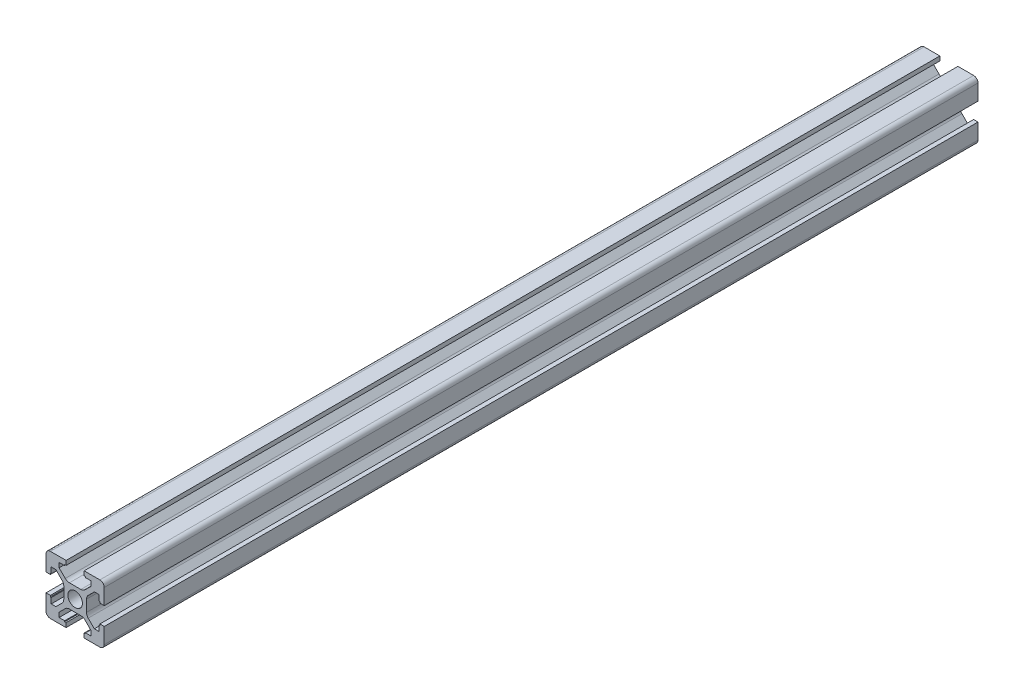
SolidWorks part; units mm, degrees
material "6063-T5"
ref_plane "Front Plane" through (0, 0, 0) normal (0, 0, 1) x (1, 0, 0)
ref_plane "Top Plane" through (0, 0, 0) normal (0, 1, 0) x (1, 0, 0)
ref_plane "Right Plane" through (0, 0, 0) normal (1, 0, 0) x (0, 0, -1)
sketch "Sketch1" plane through (0, 0, 0) normal (0, 0, 1) x (1, 0, 0)
  line L0 (0, 0) -> (0, 15) construction
  line L1 (-10, 10) -> (0, 10) construction
  line L2 (-10, 10) -> (-10, 0) construction
  line L3 (1.9716, 3.9) -> (-1.9716, 3.9)
  line L4 (-3.3858, 4.4858) -> (-5.5, 6.6)
  line L5 (0, 0) -> (-15, 0) construction
  line L6 (-5.5, 6.6) -> (-5.5, 8.2)
  line L7 (-5.5, 8.2) -> (-3.6, 8.2)
  line L8 (-3.6, 8.2) -> (-3.6, 8.5)
  line L9 (-3.6, 8.5) -> (-3.1, 8.5)
  line L10 (-3.1, 8.5) -> (-3.1, 10)
  line L11 (-3.1, 10) -> (-8.5, 10)
  line L12 (-10, 8.5) -> (-10, 3.1)
  line L13 (-10, 3.1) -> (-8.5, 3.1)
  line L14 (-8.5, 3.1) -> (-8.5, 3.6)
  line L15 (-8.5, 3.6) -> (-8.2, 3.6)
  line L16 (-8.2, 3.6) -> (-8.2, 5.5)
  line L17 (-8.2, 5.5) -> (-6.6, 5.5)
  line L18 (-6.6, 5.5) -> (-4.4858, 3.3858)
  line L19 (-3.9, 1.9716) -> (-3.9, -1.9716)
  line L20 (3.9, 1.9716) -> (3.9, -1.9716)
  line L21 (6.6, 5.5) -> (4.4858, 3.3858)
  line L22 (8.2, 5.5) -> (6.6, 5.5)
  line L23 (8.2, 3.6) -> (8.2, 5.5)
  line L24 (8.5, 3.6) -> (8.2, 3.6)
  line L25 (8.5, 3.1) -> (8.5, 3.6)
  line L26 (10, 3.1) -> (8.5, 3.1)
  line L27 (10, 8.5) -> (10, 3.1)
  line L28 (3.1, 10) -> (8.5, 10)
  line L29 (3.1, 8.5) -> (3.1, 10)
  line L30 (3.6, 8.5) -> (3.1, 8.5)
  line L31 (3.6, 8.2) -> (3.6, 8.5)
  line L32 (5.5, 8.2) -> (3.6, 8.2)
  line L33 (5.5, 6.6) -> (5.5, 8.2)
  line L34 (3.3858, 4.4858) -> (5.5, 6.6)
  line L35 (6.6, -5.5) -> (4.4858, -3.3858)
  line L36 (8.2, -5.5) -> (6.6, -5.5)
  line L37 (8.2, -3.6) -> (8.2, -5.5)
  line L38 (8.5, -3.6) -> (8.2, -3.6)
  line L39 (8.5, -3.1) -> (8.5, -3.6)
  line L40 (10, -3.1) -> (8.5, -3.1)
  line L41 (10, -8.5) -> (10, -3.1)
  line L42 (3.1, -10) -> (8.5, -10)
  line L43 (3.1, -8.5) -> (3.1, -10)
  line L44 (3.6, -8.5) -> (3.1, -8.5)
  line L45 (3.6, -8.2) -> (3.6, -8.5)
  line L46 (5.5, -8.2) -> (3.6, -8.2)
  line L47 (5.5, -6.6) -> (5.5, -8.2)
  line L48 (3.3858, -4.4858) -> (5.5, -6.6)
  line L49 (1.9716, -3.9) -> (-1.9716, -3.9)
  line L50 (-3.3858, -4.4858) -> (-5.5, -6.6)
  line L51 (-5.5, -6.6) -> (-5.5, -8.2)
  line L52 (-5.5, -8.2) -> (-3.6, -8.2)
  line L53 (-3.6, -8.2) -> (-3.6, -8.5)
  line L54 (-3.6, -8.5) -> (-3.1, -8.5)
  line L55 (-3.1, -8.5) -> (-3.1, -10)
  line L56 (-3.1, -10) -> (-8.5, -10)
  line L57 (-10, -8.5) -> (-10, -3.1)
  line L58 (-10, -3.1) -> (-8.5, -3.1)
  line L59 (-8.5, -3.1) -> (-8.5, -3.6)
  line L60 (-8.5, -3.6) -> (-8.2, -3.6)
  line L61 (-8.2, -3.6) -> (-8.2, -5.5)
  line L62 (-8.2, -5.5) -> (-6.6, -5.5)
  line L63 (-6.6, -5.5) -> (-4.4858, -3.3858)
  circle A0 centre (0, 0) radius 2.5
  arc A1 (-10, -8.5) -> (-8.5, -10) centre (-8.5, -8.5) ccw
  arc A2 (8.5, -10) -> (10, -8.5) centre (8.5, -8.5) ccw
  arc A3 (10, 8.5) -> (8.5, 10) centre (8.5, 8.5) ccw
  arc A4 (-8.5, 10) -> (-10, 8.5) centre (-8.5, 8.5) ccw
  arc A5 (-3.3858, -4.4858) -> (-1.9716, -3.9) centre (-1.9716, -5.9) cw
  arc A6 (1.9716, -3.9) -> (3.3858, -4.4858) centre (1.9716, -5.9) cw
  arc A7 (4.4858, -3.3858) -> (3.9, -1.9716) centre (5.9, -1.9716) cw
  arc A8 (3.9, 1.9716) -> (4.4858, 3.3858) centre (5.9, 1.9716) cw
  arc A9 (1.9716, 3.9) -> (3.3858, 4.4858) centre (1.9716, 5.9) ccw
  arc A10 (-1.9716, 3.9) -> (-3.3858, 4.4858) centre (-1.9716, 5.9) cw
  arc A11 (-4.4858, 3.3858) -> (-3.9, 1.9716) centre (-5.9, 1.9716) cw
  arc A12 (-3.9, -1.9716) -> (-4.4858, -3.3858) centre (-5.9, -1.9716) cw
  point P40 (0, 3.9)
  point P41 (3.9, 0)
  point P70 (-3.9, 0)
  point P72 (-10, -10)
  point P75 (10, -10)
  point P78 (10, 10)
  point P84 (-2.8, -3.9)
  point P87 (2.8, -3.9)
  point P90 (3.9, -2.8)
  point P93 (3.9, 2.8)
  point P96 (2.8, 3.9)
  point P99 (-2.8, 3.9)
  point P102 (-3.9, 2.8)
  point P105 (-3.9, -2.8)
  dimension "D3" = 5
  dimension "D14" = 1.5
  dimension "D15" = 2
  dimension "D1" = 10
  dimension "D2" = 10
  dimension "D4" = 15
  dimension "D5" = 5.5
  dimension "D6" = 3.4
  dimension "D7" = 6.1
  dimension "D8" = 6.1
  dimension "D9" = 3.1
  dimension "D10" = 3.6
  dimension "D11" = 1.5556
  dimension "D12" = 1.8
  dimension "D13" = 1.5
extrude "Boss-Extrude1" add sketch "Sketch1" along normal blind 300
